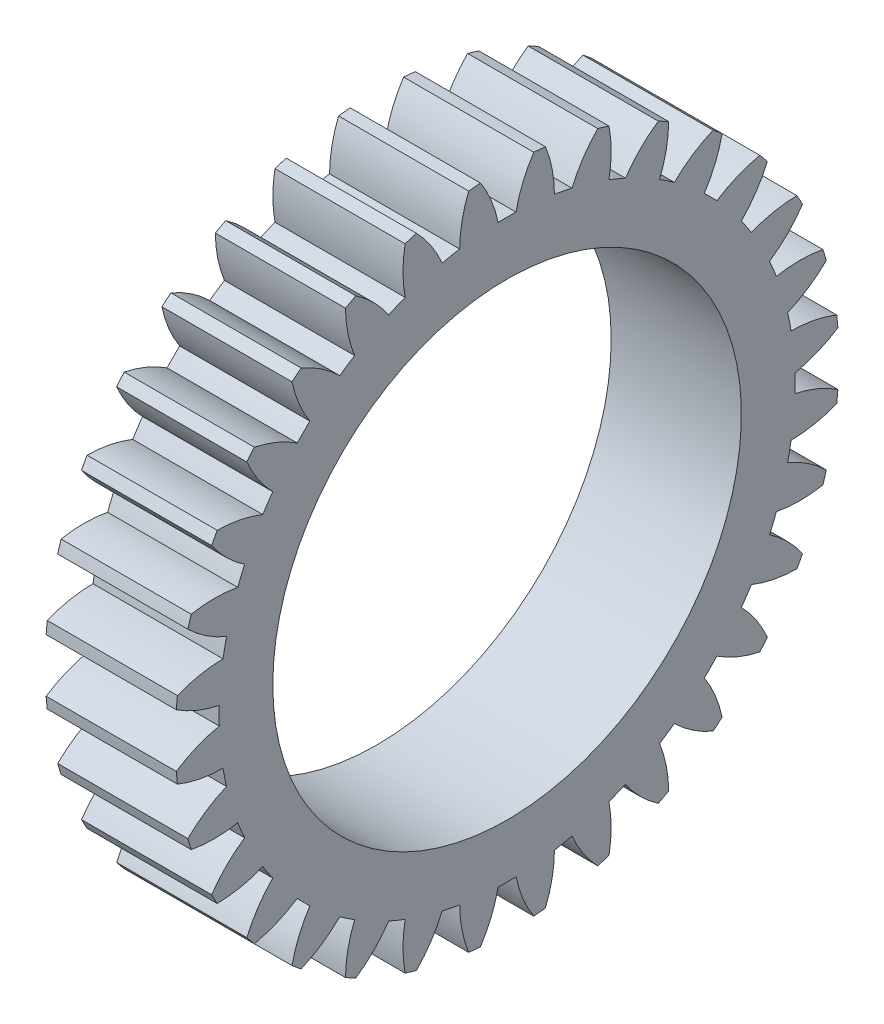
SolidWorks part; units mm, degrees
ref_plane "Plane1" through (0, 0, 0) normal (0, 0, 1) x (1, 0, 0)
ref_plane "Plane2" through (0, 0, 0) normal (0, 1, 0) x (1, 0, 0)
ref_plane "Plane3" through (0, 0, 0) normal (1, 0, 0) x (0, 0, -1)
sketch "HoldingSke" plane through (0, 0, 0) normal (0, 1, 0) x (1, 0, 0)
  line L0 (0, 0) -> (0.5654, -0.3533)
  line L1 (-15, 0) -> (100, 0) construction
  line L2 (0, 0) -> (-2.1039, 2.3779)
  line L3 (0, 0) -> (-11.863, 4.5341)
  line L4 (0, 0) -> (7.3237, 4.5764)
  line L5 (0, 0) -> (-46.8476, -17.4728)
  line L6 (0, 0) -> (-8.2896, -5.593)
  line L7 (-2.1039, 2.3779) -> (8.6586, 51.2059)
  line L8 (-76.2, 54.61) -> (-72.9, 54.61)
  line L9 (-71.009, 38.7566) -> (-53.1078, 45.2721)
  line L10 (-76.2, 71.12) -> (104.1128, 71.12)
  line L11 (0, 0) -> (-10, 0)
  line L12 (-76.2, 101.6) -> (-76.147, 101.6)
  line L13 (24.9733, 27.94) -> (52.9518, 28.4284)
  line L14 (24.9733, 27.94) -> (24.9743, 27.94)
  line L15 (24.9733, 27.94) -> (100.4006, 29.5858)
  line L16 (-63.627, -1.5) -> (-12.827, -1.5)
  circle A0 centre (0, 0) radius 18
  circle A1 centre (0, 0) radius 22.124
  circle A2 centre (0, 0) radius 37.5
  circle A3 centre (0, 0) radius 18
  dimension "MHD" = 44.248
  dimension "Hub_dia" = 75
  dimension "Bore" = 36
  dimension "MBD" = 36
  dimension "Num_teeth" = 32
  dimension "Pitch" = 0.6667
  dimension "Overall_len" = 50
  dimension "Show_teeth" = 32
  dimension "Thickness" = 10
  dimension "OAL" = 50.0001
  dimension "T_dim" = 3.3
  dimension "Ap" = 20
  dimension "H" = 19.05
  dimension "Pitch_radius" = 180.3128
  dimension "Width" = 10
  dimension "Backlash" = 0.053
  dimension "Addendum_fac" = 1
  dimension "Dedendum_fac" = 1.25
  dimension "Clearance_fac" = 0.25
  dimension "Dedendum_add" = 0.001
  dimension "Module" = 1.5
sketch "BasProSke" plane through (0, 0, 0) normal (0, 1, 0) x (1, 0, 0)
  line L0 (-10, 0) -> (60, 0) construction
  line L1 (0, 0) -> (0, 25.5)
  line L2 (0, 0) -> (10, 0)
  line L3 (10, 0) -> (10, 25.5)
  line L4 (10, 25.5) -> (0, 25.5)
  dimension "Thickness" = 10
  dimension "Diameter" = 51
revolve "Base-Revolve" add sketch "BasProSke" angle 360 about L0
sketch "TooCutSke" plane through (0, 0, 0) normal (1, 0, 0) x (0, 0, -1)
  line L1 (0, 0) -> (0, 107) construction
  line L2 (0, 0) -> (-1.2704, 23.9664) construction
  line L3 (0, 0) -> (-4.7, 47.72) construction
  line L4 (-1.2704, 23.9664) -> (-2.35, 23.86) construction
  arc A0 (0.6867, 22.1133) -> (-0.6867, 22.1133) centre (0, 0) ccw
  arc A1 (2.0647, 25.4418) -> (-2.0647, 25.4418) centre (0, 0) ccw
  circle A2 centre (0, 0) radius 24 construction
  circle A3 centre (0, 0) radius 22.5526 construction
  arc A4 (-0.6867, 22.1133) -> (-2.0647, 25.4418) centre (-10.0881, 20.1706) ccw
  arc A5 (2.0647, 25.4418) -> (0.6867, 22.1133) centre (10.0881, 20.1706) ccw
  dimension "Root_dia" = 44.248
  dimension "Overcut_dia" = 51.0508
  dimension "Pitch_dia" = 48
  dimension "Base_dia" = 45.1052
  dimension "Flank_rad" = 9.6
  dimension "Half_ang" = 5.625
  dimension "Half_CT" = 1.0849
extrude "ToothCut" cut sketch "TooCutSke" along normal through all
fillet "Breaks" [suppressed] radius 0.03
fillet "RootFillets" [suppressed] radius 0.376
pattern_circular "TeethCuts" count 32 every 11.25 about axis through (-10, 0, 0) along (1, 0, 0) of "ToothCut", "RootFillets", "Breaks"
sketch "HubNeaOneSke" plane through (0, 0, 0) normal (-1, 0, 0) x (0, 0, 1)
  circle A0 centre (0, 0) radius 22.124
  dimension "Diameter" = 44.248
extrude "HubNearOne" [suppressed] add sketch "HubNeaOneSke" along normal blind 40.0001
sketch "HubNeaBotSke" plane through (0, 0, 0) normal (-1, 0, 0) x (0, 0, 1)
  circle A0 centre (0, 0) radius 22.124
  dimension "Diameter" = 44.248
extrude "HubNearBoth" [suppressed] add sketch "HubNeaBotSke" along normal blind 20
ref_plane "FarPln" through (10, 0, 0) normal (1, 0, 0) x (0, 0, -1)
sketch "HubFarSke" plane through (10, 0, 0) normal (1, 0, 0) x (0, 0, -1)
  circle A0 centre (0, 0) radius 22.124
  dimension "Diameter" = 44.248
extrude "HubFar" [suppressed] add sketch "HubFarSke" along normal blind 20
sketch "BorSke" plane through (0, 0, 0) normal (1, 0, 0) x (0, 0, -1)
  circle A0 centre (0, 0) radius 18
  dimension "Diameter" = 36
extrude "Bore" cut sketch "BorSke" along normal mid plane 100.0001
sketch "KeySke" plane through (0, 0, 0) normal (1, 0, 0) x (0, 0, -1)
  line L0 (-5, 0) -> (-5, 21.3)
  line L1 (-5, 21.3) -> (5, 21.3)
  line L2 (5, 21.3) -> (5, 0)
  line L3 (0, 0) -> (0, 34) construction
  line L4 (-5, 0) -> (5, 0)
  dimension "Width" = 10
  dimension "Offset" = 21.3
extrude "Keyway" [suppressed] cut sketch "KeySke" along normal mid plane 100.0001
pattern_circular "Keyway2" [suppressed] count 2 every 90 about axis through (-10, 0, 0) along (1, 0, 0)
equation "' \"Module@HoldingSke\" = 6.35"
equation "' \"Num_teeth@HoldingSke\" = 12"
equation "' \"Ap@HoldingSke\" =  20"
equation "' \"Ap@HoldingSke\" = 20"
equation "' \"Width@HoldingSke\" = 0.5 * 25.4"
equation "' \"Hub_dia@HoldingSke\"= 1 * 25.4"
equation "' \"Hub_dia@HoldingSke\" = 1 * 25.4"
equation "' \"Overall_len@HoldingSke\" = 1.0 * 25.4"
equation "' \"Bore@HoldingSke\" = 0.75 * 25.4"
equation "' \"T_dim@HoldingSke\" = 0.1 * 25.4"
equation "' \"Width@KeySke\" = 0.25 * 25.4"
equation "' \"Show_teeth@HoldingSke\" = 13"
equation "' \"Backlash@HoldingSke\" = 0.009 * 25.4"
equation "' \"Addendum_fac@HoldingSke\" = 1.0"
equation "' \"Dedendum_fac@HoldingSke\" = 1.25"
equation "' \"Dedendum_add@HoldingSke\" = 0.00005 * 25.4"
equation "' \"Clearance_fac@HoldingSke\" = 0.25"
equation "\"Pitch@HoldingSke\" = 1 / \"Module@HoldingSke\""
equation "\"Overcut_dia@TooCutSke\" = (\"Num_teeth@HoldingSke\" + 2 * \"Addendum_fac@HoldingSke\") / \"Pitch@HoldingSke\" + 0.002 * 25.4"
equation "\"Pitch_dia@TooCutSke\" = \"Num_teeth@HoldingSke\" / \"Pitch@HoldingSke\""
equation "\"Base_dia@TooCutSke\" = \"Num_teeth@HoldingSke\" / \"Pitch@HoldingSke\" * cos((\"Ap@HoldingSke\"  * 3.14159265 / 180))"
equation "\"Root_dia@TooCutSke\" = (\"Num_teeth@HoldingSke\" + 2) / \"Pitch@HoldingSke\" - 2 * (\"Addendum_fac@HoldingSke\" + \"Dedendum_fac@HoldingSke\") / \"Pitch@HoldingSke\" - \"Dedendum_add@HoldingSke\" * 2"
equation "\"Half_ang@TooCutSke\" = 180 / \"Num_teeth@HoldingSke\""
equation "\"Half_CT@TooCutSke\" = \"Num_teeth@HoldingSke\" / \"Pitch@HoldingSke\" * sin((3.14159265 / 2 / \"Num_teeth@HoldingSke\")) / 2 - 7 * \"Backlash@HoldingSke\" / 4"
equation "\"Flank_rad@TooCutSke\" = \"Num_teeth@HoldingSke\" / \"Pitch@HoldingSke\" / 5"
equation "\"Radius@RootFillets\" = \"Clearance_fac@HoldingSke\" / \"Pitch@HoldingSke\" + \"Dedendum_add@HoldingSke\""
equation "\"Break_rad@Breaks\" = 0.02 / \"Pitch@HoldingSke\""
equation "\"Thickness@HoldingSke\" = \"Width@HoldingSke\""
equation "\"OAL@HoldingSke\" = \"Thickness@HoldingSke\""
equation "\"MHD@HoldingSke\" = (\"Num_teeth@HoldingSke\" + 2) / \"Pitch@HoldingSke\" - 2 * (\"Addendum_fac@HoldingSke\" + \"Dedendum_fac@HoldingSke\")  / \"Pitch@HoldingSke\" - \"Dedendum_add@HoldingSke\" * 2"
equation "\"MBD@HoldingSke\" = (\"Num_teeth@HoldingSke\" + 2) / \"Pitch@HoldingSke\" - 2 * (\"Addendum_fac@HoldingSke\" + \"Dedendum_fac@HoldingSke\")  / \"Pitch@HoldingSke\" - \"Dedendum_add@HoldingSke\" * 2 - 0.002 * 25.4"
equation "\"MHD@HoldingSke\" = ((sgn( \"MHD@HoldingSke\" - \"Hub_dia@HoldingSke\" )-1)*( \"MHD@HoldingSke\" - \"Hub_dia@HoldingSke\" ))/-2+ \"Hub_dia@HoldingSke\""
equation "\"MBD@HoldingSke\" = ((sgn( \"MBD@HoldingSke\" - \"Bore@HoldingSke\" )-1)*( \"MBD@HoldingSke\" - \"Bore@HoldingSke\" ))/-2+ \"Bore@HoldingSke\""
equation "\"OAL@HoldingSke\" = ((sgn( \"OAL@HoldingSke\" - \"Overall_len@HoldingSke\" )+1)*( \"OAL@HoldingSke\" - \"Overall_len@HoldingSke\" ))/2 + \"Overall_len@HoldingSke\" + 0.000002 * 25.4"
equation "\"Num_teeth@TeethCuts\" = int( \"Show_teeth@HoldingSke\" ) + 1"
equation "\"Num_teeth@TeethCuts\" = ((sgn( \"Num_teeth@TeethCuts\" - \"Num_teeth@HoldingSke\" )-1)*( \"Num_teeth@TeethCuts\" - \"Num_teeth@HoldingSke\" ))/-2+ \"Num_teeth@HoldingSke\""
equation "\"Num_teeth@TeethCuts\" = ((sgn( \"Num_teeth@TeethCuts\" - 2.0)+1)*( \"Num_teeth@TeethCuts\" - 2.0))/2 +2.0"
equation "\"Angle@TeethCuts\" = 360.0 / \"Num_teeth@HoldingSke\""
equation "\"Diameter@BasProSke\" = (\"Num_teeth@HoldingSke\" + 2 * \"Addendum_fac@HoldingSke\") / \"Pitch@HoldingSke\""
equation "\"Thickness@BasProSke\"  = \"Thickness@HoldingSke\""
equation "' \"Fillet_rad@BasProSke\" =  \"Thickness@HoldingSke\" * 0.05"
equation "' \"Fillet_rad@BasProSke\" = \"Thickness@HoldingSke\" * 0.05"
equation "\"MHD@HoldingSke\" = ((sgn( \"MHD@HoldingSke\" - \"Root_dia@TooCutSke\" )-1)*( \"MHD@HoldingSke\" - \"Root_dia@TooCutSke\" ))/-2+ \"Root_dia@TooCutSke\""
equation "\"Diameter@HubNeaOneSke\" = \"MHD@HoldingSke\""
equation "\"Length@HubNearOne\" = \"OAL@HoldingSke\" - \"Thickness@BasProSke\""
equation "\"Diameter@HubNeaBotSke\" = \"MHD@HoldingSke\""
equation "\"Length@HubNearBoth\" = ( \"OAL@HoldingSke\" - \"Thickness@BasProSke\" ) / 2.0"
equation "\"Thickness@FarPln\" = \"Thickness@BasProSke\""
equation "\"Diameter@HubFarSke\" = \"MHD@HoldingSke\""
equation "\"Length@HubFar\" = ( \"OAL@HoldingSke\" - \"Thickness@BasProSke\" ) / 2.0"
equation "\"Diameter@BorSke\" = \"MBD@HoldingSke\""
equation "\"D1@Bore\" = \"OAL@HoldingSke\" * 2.0"
equation "\"D1@Keyway\" = \"OAL@HoldingSke\" * 2.0"
equation "\"Offset@KeySke\" = \"T_dim@HoldingSke\" + \"MBD@HoldingSke\" / 2.0"
